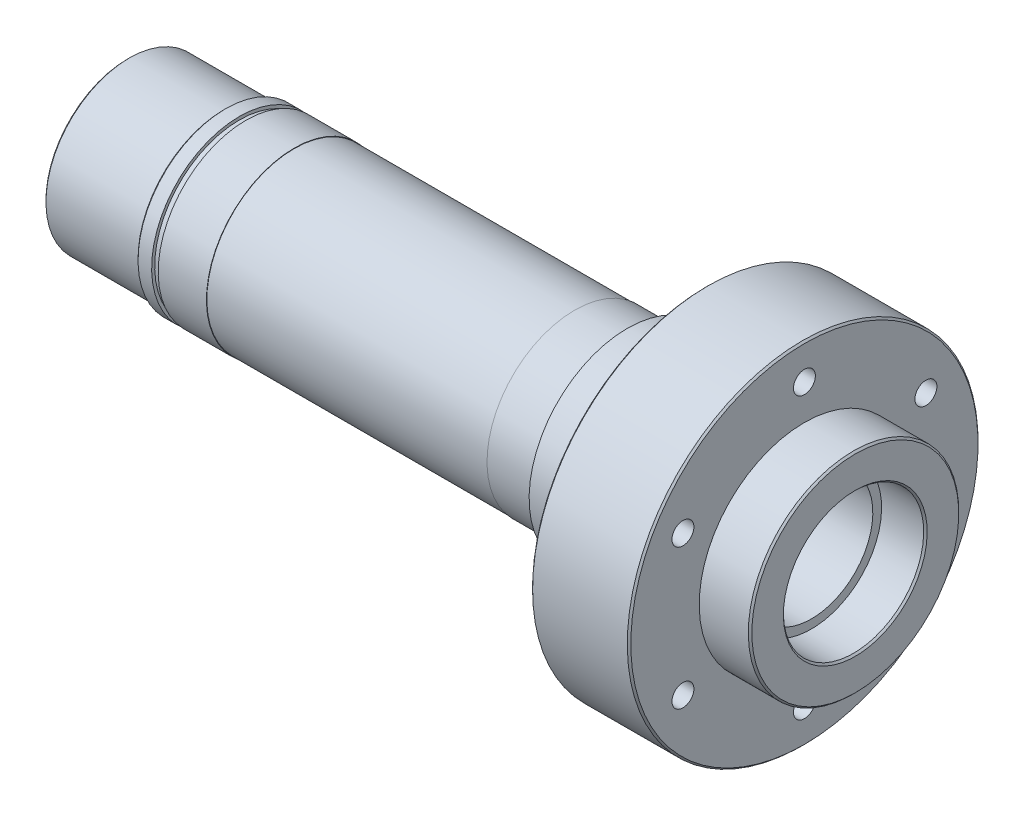
SolidWorks part; units mm, degrees
ref_plane "Piano frontale" through (0, 0, 0) normal (0, 0, 1) x (1, 0, 0)
ref_plane "Piano superiore" through (0, 0, 0) normal (0, 1, 0) x (1, 0, 0)
ref_plane "Piano destro" through (0, 0, 0) normal (1, 0, 0) x (0, 0, -1)
sketch "Schizzo1" plane through (0, 0, 0) normal (0, 0, 1) x (1, 0, 0)
  line L0 (0, 0) -> (-49, 0)
  line L1 (-271.3697, 40) -> (-246.3697, 40)
  line L2 (-271.3697, 40) -> (-271.3697, 47.5)
  line L3 (-271.3697, 47.5) -> (-216.3697, 47.5)
  line L4 (-216.3697, 47.5) -> (-216.3697, 50)
  line L5 (-216.3697, 50) -> (-207.6197, 50)
  line L6 (-207.6197, 50) -> (-207.6197, 48.25)
  line L7 (-207.6197, 48.25) -> (-203.8697, 48.25)
  line L8 (-246.3697, 40) -> (-246.3697, 35)
  line L9 (-246.3697, 35) -> (118.6303, 35)
  line L10 (118.6303, 35) -> (118.6303, 40)
  line L11 (118.6303, 40) -> (143.6303, 40)
  line L12 (143.6303, 40) -> (143.6303, 60)
  line L13 (143.6303, 60) -> (114.6303, 60)
  line L14 (114.6303, 60) -> (114.6303, 100)
  line L15 (114.6303, 100) -> (58.6303, 100)
  line L16 (58.6303, 100) -> (58.6303, 60)
  line L17 (58.6303, 60) -> (36.6303, 60)
  line L18 (36.6303, 60) -> (31.6724, 56)
  line L19 (31.6724, 56) -> (13.6303, 56)
  line L20 (13.6303, 56) -> (13.6303, 50)
  line L21 (-203.8697, 48.25) -> (-203.8697, 50)
  line L22 (-203.8697, 50) -> (-176.3697, 50)
  line L23 (-176.3697, 50) -> (-176.3697, 49.75)
  line L24 (-176.3697, 49.75) -> (-16.3697, 49.75)
  line L25 (13.6303, 50) -> (-16.3697, 50)
  line L26 (-16.3697, 50) -> (-16.3697, 49.75)
  dimension "D1" = 35
  dimension "D2" = 40
  dimension "D3" = 47.5
  dimension "D4" = 48.25
  dimension "D5" = 50
  dimension "D6" = 49.75
  dimension "D7" = 29
  dimension "D8" = 25
  dimension "D9" = 25
  dimension "D10" = 365
  dimension "D11" = 56
  dimension "D12" = 22
  dimension "D13" = 45
  dimension "D14" = 30
  dimension "D15" = 3.75
  dimension "D16" = 27.5
  dimension "D17" = 160
  dimension "D18" = 55
  dimension "D19" = 40
  dimension "D20" = 60
  dimension "D21" = 100
  dimension "D22" = 50
  dimension "D23" = 60
  dimension "D24" = 56
  dimension "D25" = 50
  dimension "D26" = 23
revolve "Rivoluzione1" add sketch "Schizzo1" angle 360 about L0
chamfer "Smusso1" distance 1 angle 45 3 edges at (114.6303, 100, 0) (143.6303, 60, 0) (58.6303, 100, 0)
chamfer "Smusso2" distance 1 angle 45 4 edges at (-216.3697, 50, 0) (-271.3697, 40, 0) (-271.3697, 47.5, 0) (143.6303, 40, 0)
sketch "Schizzo6" plane through (114.6303, 0, 0) normal (1, 0, 0) x (0, 0, -1)
  circle A0 centre (0, -80) radius 6.25
  dimension "D1" = 80
  dimension "D2" = 12.5
extrude "Taglio-Estrusione1" cut sketch "Schizzo6" against normal up to surface (56 mm away) up to face at (58.6303, -99, 0)
pattern_circular "RipetizioneCircolare1" count 6 over 360 about axis through (0, 0, 0) along (1, 0, 0) of "Taglio-Estrusione1"
